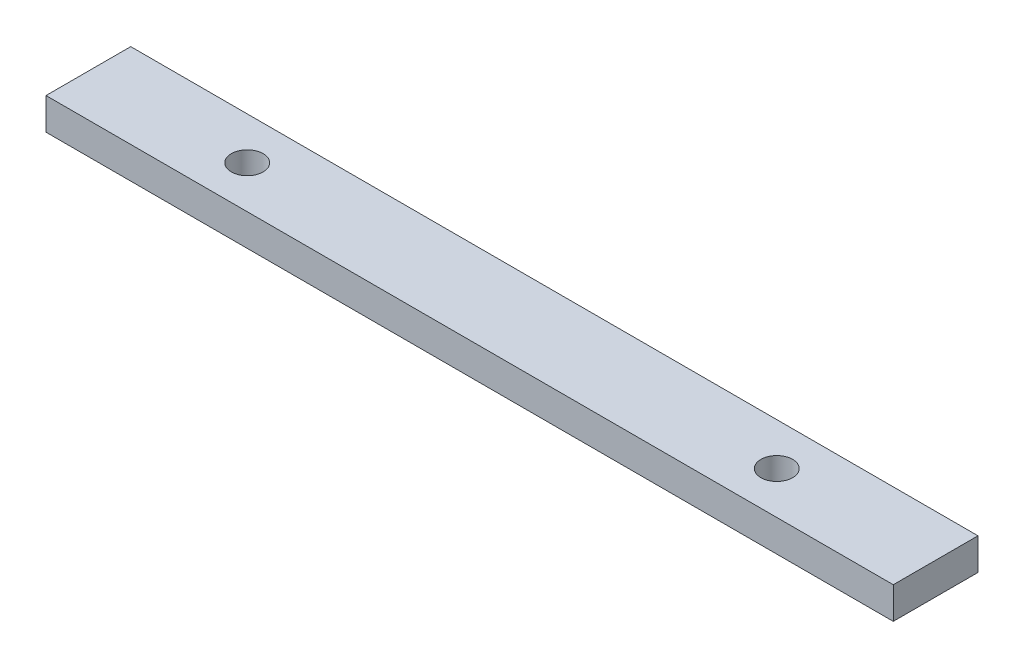
SolidWorks part; units mm, degrees
ref_plane "Alzado" through (0, 0, 0) normal (0, 0, 1) x (1, 0, 0)
ref_plane "Planta" through (0, 0, 0) normal (0, 1, 0) x (1, 0, 0)
ref_plane "Vista lateral" through (0, 0, 0) normal (1, 0, 0) x (0, 0, -1)
sketch "Croquis1" plane through (0, 0, 0) normal (0, 1, 0) x (1, 0, 0)
  line L0 (-40, 4) -> (40, 4)
  line L3 (40, -4) -> (-40, -4)
  line L4 (-40, 4) -> (-40, -4)
  line L5 (40, 4) -> (40, -4)
  circle A4 centre (25, 0) radius 1.5
  circle A5 centre (-25, 0) radius 1.5
  point P0 (40, 0)
  dimension "D2" = 80
  dimension "D8" = 3
  dimension "D10" = 3
  dimension "D3" = 4
  dimension "D4" = 4
  dimension "D5" = 40
  dimension "D11" = 25
  dimension "D12" = 25
extrude "Saliente-Extruir1" add sketch "Croquis1" along normal blind 3
